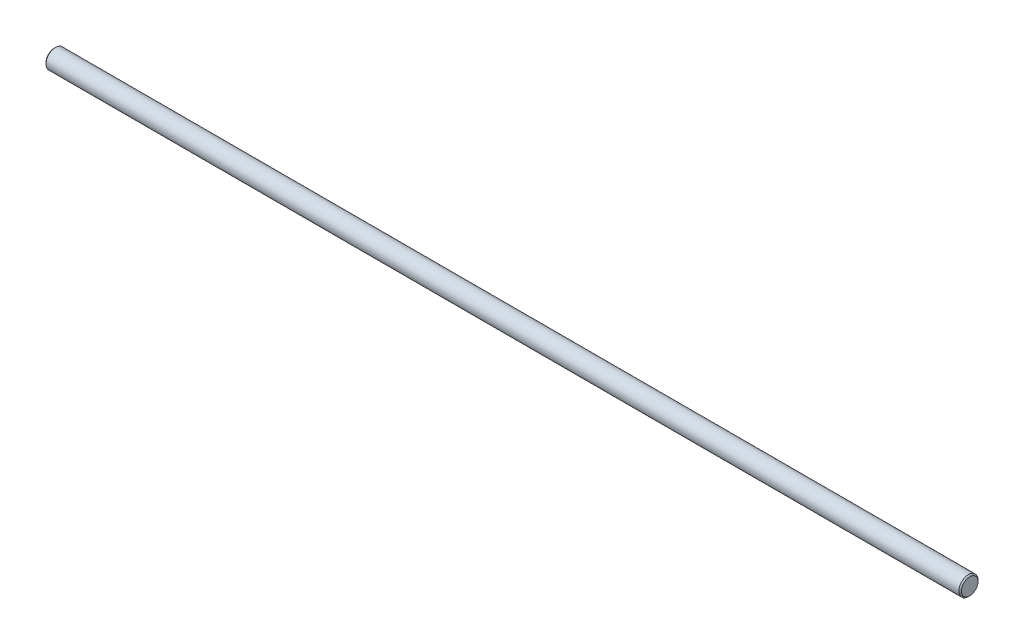
SolidWorks part; units mm, degrees
material "Plain Carbon Steel"
ref_plane "Front Plane" through (0, 0, 0) normal (0, 0, 1) x (1, 0, 0)
ref_plane "Top Plane" through (0, 0, 0) normal (0, 1, 0) x (1, 0, 0)
ref_plane "Right Plane" through (0, 0, 0) normal (1, 0, 0) x (0, 0, -1)
sketch "Sketch1" plane through (0, 0, 0) normal (1, 0, 0) x (0, 0, -1)
  circle A0 centre (0, 0) radius 9.525
  dimension "D1" = 19.05
extrude "Boss-Extrude1" add sketch "Sketch1" along normal mid plane 914.4
chamfer "Chamfer1" distance 1.27 angle 45 2 edges at (457.2, 0, -9.525) (-457.2, 0, -9.525)
